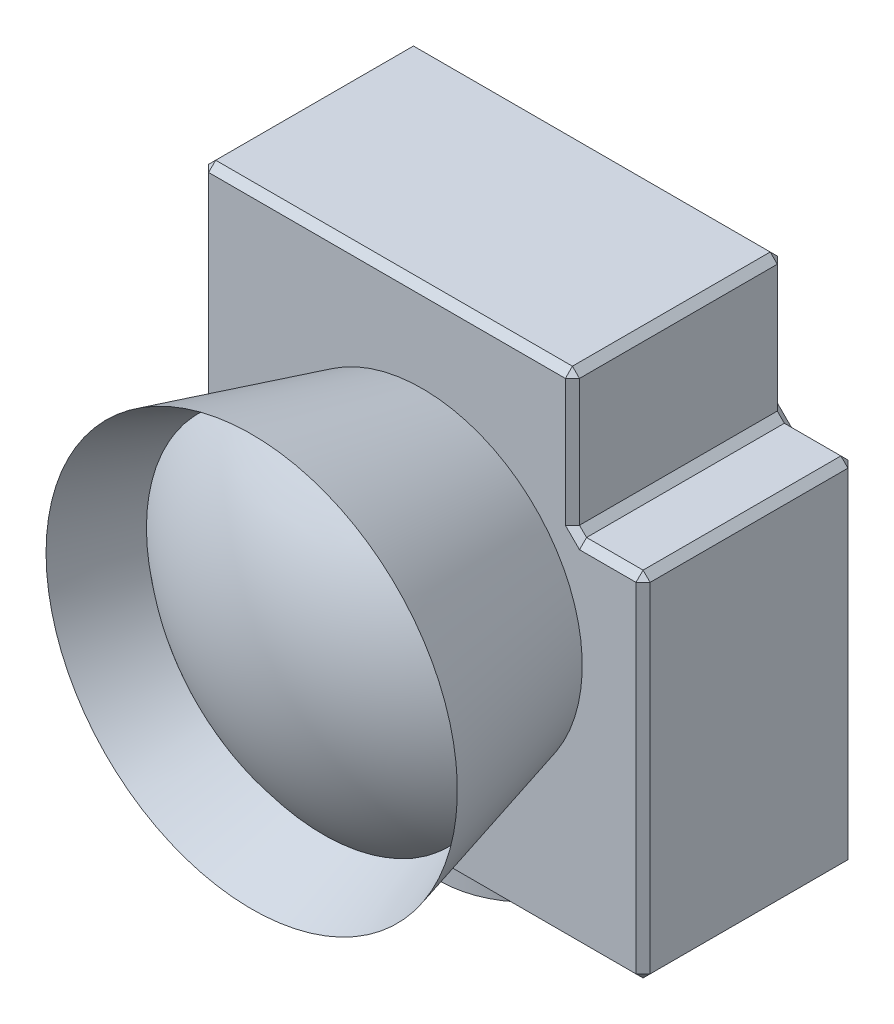
SolidWorks part; units mm, degrees
ref_plane "Front Plane" through (0, 0, 0) normal (0, 0, 1) x (1, 0, 0)
ref_plane "Top Plane" through (0, 0, 0) normal (0, 1, 0) x (1, 0, 0)
ref_plane "Right Plane" through (0, 0, 0) normal (1, 0, 0) x (0, 0, -1)
sketch "Sketch1" plane through (0, 0, 0) normal (0, 0, 1) x (1, 0, 0)
  line L1 (21.25, 35) -> (-31.25, 35)
  line L2 (31.25, 15) -> (31.25, -35)
  line L3 (31.25, -35) -> (-31.25, -35)
  line L4 (-31.25, 35) -> (-31.25, -35)
  line L6 (31.25, -35) -> (-31.25, 35) construction
  line L9 (31.25, 15) -> (21.25, 15)
  line L10 (21.25, 35) -> (21.25, 15)
  point P0 (0, 0)
  point P2 (0, 0)
  dimension "D1" = 70
  dimension "D2" = 62.5
  dimension "D3" = 20
  dimension "D4" = 10
extrude "Boss-Extrude1" add sketch "Sketch1" along normal mid plane 30
sketch "Sketch2" plane through (0, -35, 0) normal (0, -1, 0) x (1, 0, 0)
  circle A0 centre (0, 0) radius 12.5
  dimension "D1" = 25
extrude "Boss-Extrude2" add sketch "Sketch2" along normal mid plane 8
chamfer "Chamfer1" distance 1 angle 45 18 edges at (-31.25, -35, 0) (31.25, -35, 0) (31.25, 15, 0) (21.25, 15, 0) (21.25, 35, 0) (-5, 35, 15) (21.25, 25, 15) (26.25, 15, 15) (31.25, -10, 15) (0, -35, 15) (-31.25, 0, 15) (-31.25, 35, 0) (-5, 35, -15) (21.25, 25, -15) (26.25, 15, -15) (31.25, -10, -15) (0, -35, -15) (-31.25, 0, -15)
sketch "Sketch4" plane through (0, 0, 0) normal (0, 1, 0) x (1, 0, 0)
  line L0 (-22.6403, -15) -> (-29.1107, -39.1481)
  line L1 (20.25, -15) -> (-30.25, -15) construction
  line L2 (-29.1107, -39.1481) -> (-19.474, -15)
  line L3 (-22.6403, -15) -> (-19.474, -15)
  line L4 (0, 0) -> (0, -50000) construction
  line L5 (0, 0) -> (50000, 0) construction
  dimension "D1" = 75
  dimension "D2" = 25
  dimension "D3" = 26
revolve "Revolve1" add sketch "Sketch4" angle 360 about L4
sketch "Sketch5" plane through (0, 0, 0) normal (0, 1, 0) x (1, 0, 0)
  line L0 (-19.474, -15) -> (-29.1107, -39.1481) construction
  line L1 (0, -33.7502) -> (0, -38.3214)
  arc A0 (-25.0583, -28.9933) -> (0, -38.3214) centre (0, 0) ccw
  spline S0 degree 2 poles (-25.0583, -28.9933) (-12.5291, -33.7502) (0, -33.7502) knots 0 0 0 0.5 0.5 0.5
  dimension "D1" = 38.3214
  dimension "D2" = 33.7502
revolve "Revolve2" add sketch "Sketch5" angle 360 about L4
